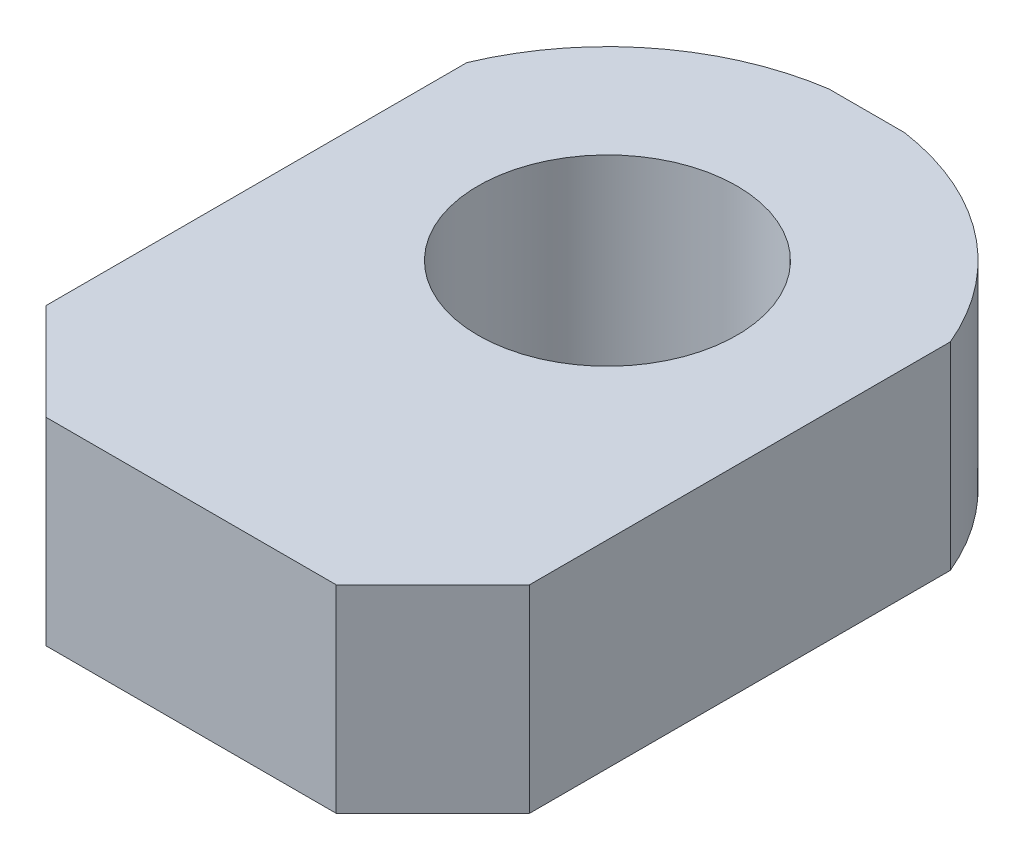
SolidWorks part; units mm, degrees
ref_plane "Front Plane" through (0, 0, 0) normal (0, 0, 1) x (1, 0, 0)
ref_plane "Top Plane" through (0, 0, 0) normal (0, 1, 0) x (1, 0, 0)
ref_plane "Right Plane" through (0, 0, 0) normal (1, 0, 0) x (0, 0, -1)
sketch "Sketch1" plane through (0, 0, 0) normal (0, 1, 0) x (1, 0, 0)
  line L0 (-14.29, 5.978) -> (-14.29, -18.894)
  line L1 (-14.29, -18.894) -> (-8.574, -24.61)
  line L2 (-8.574, -24.61) -> (8.574, -24.61)
  line L3 (8.574, -24.61) -> (14.29, -18.894)
  line L4 (14.29, -18.894) -> (14.29, 5.978)
  line L5 (-2.2206, 15.33) -> (2.2206, 15.33)
  line L6 (0, 0) -> (0, 34.0054) construction
  arc A0 (-14.29, 5.978) -> (-2.2206, 15.33) centre (0, 0) cw
  arc A1 (2.2206, 15.33) -> (14.29, 5.978) centre (0, 0) cw
  circle A2 centre (0, 0) radius 7.65
  dimension "D2" = 39.94
  dimension "D5" = 15.49
  dimension "D6" = 15.3
  dimension "D1" = 28.58
  dimension "D3" = 15.33
  dimension "D4" = 17.148
extrude "Boss-Extrude1" add sketch "Sketch1" along normal blind 11.7
